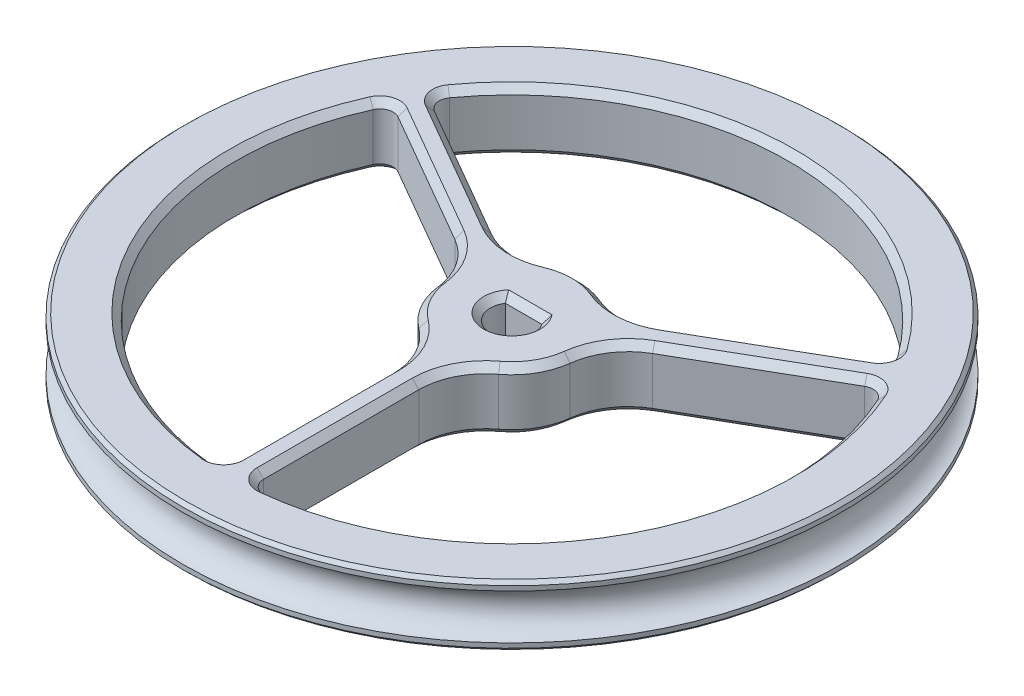
SolidWorks part; units mm, degrees
ref_plane "Front" through (0, 0, 0) normal (0, 0, 1) x (1, 0, 0)
ref_plane "Top" through (0, 0, 0) normal (0, 1, 0) x (1, 0, 0)
ref_plane "Right" through (0, 0, 0) normal (1, 0, 0) x (0, 0, -1)
sketch "Sketch1" plane through (0, 0, 0) normal (0, 1, 0) x (1, 0, 0)
  circle A0 centre (0, 0) radius 24.765
  dimension "D1" = 49.53
extrude "Boss-Extrude1" add sketch "Sketch1" along normal mid plane 4.572
sketch "Sketch2" plane through (0, 0, 0) normal (1, 0, 0) x (0, 0, -1)
  line L0 (0, 0) -> (0, 2.286) construction
  line L2 (0, 0) -> (25.065, 0) construction
  line L3 (24.765, -2.286) -> (24.765, 2.286) construction
  line L4 (24.765, 2.286) -> (-24.765, 2.286) construction
  circle A0 centre (25.065, 0) radius 1.7145
  dimension "D1" = 3.429
  dimension "D2" = 0.3
revolve "Cut-Revolve1" cut sketch "Sketch2" angle 360 about L0
sketch "Sketch3" plane through (0, 2.286, 0) normal (0, 1, 0) x (1, 0, 0)
  line L0 (1.365, 0.8854) -> (1.373, 0.873)
  line L1 (1.373, 0.873) -> (-1.373, 0.873)
  arc A0 (-1.373, 0.873) -> (1.373, 0.873) centre (0, 0) ccw
  dimension "D2" = 3.254
  dimension "D1" = 2.5
extrude "Cut-Extrude1" cut sketch "Sketch3" against normal through all contours L1 A0
sketch "Sketch4" plane through (0, 2.286, 0) normal (0, 1, 0) x (1, 0, 0)
  line L0 (0, 0) -> (21.4471, 12.3825) construction
  line L1 (0, 0) -> (0, 24.765) construction
  line L2 (0, 0) -> (-21.4471, 12.3825) construction
  line L3 (3.7426, 3.3155) -> (17.4622, 11.2365)
  line L4 (-3.7426, 3.3155) -> (-17.4622, 11.2365)
  circle A0 centre (0, 0) radius 24.765 construction
  arc A1 (-3.7426, 3.3155) -> (3.7426, 3.3155) centre (0, 0) cw
  arc A3 (-17.4622, 11.2365) -> (17.4622, 11.2365) centre (0, 0) cw
  dimension "D2" = 4
  dimension "D3" = 5
  dimension "D1" = 120
  dimension "D4" = 2
extrude "Cut-Extrude2" cut sketch "Sketch4" against normal through all
pattern_circular "CirPattern1" count 3 every 120 about axis through (0, 0, 0) along (0, 1, 0) of "Cut-Extrude2"
fillet "Fillet1" radius 5 6 edges at (3.7426, 0, -3.3155) (-3.7426, 0, -3.3155) (4.7426, 0, -1.5835) (1, 0, 4.899) (-1, 0, 4.899) (-4.7426, 0, -1.5835)
fillet "Fillet4" radius 1 6 edges at (17.4622, 0, -11.2365) (18.4622, 0, -9.5044) (-18.4622, 0, -9.5044) (-17.4622, 0, -11.2365) (1, 0, 20.7409) (-1, 0, 20.7409)
chamfer "Chamfer1" distance 0.5 angle 45 4 edges at (0, -2.286, 1.627) (0, -2.286, -0.873) (0, 2.286, 1.627) (0, 2.286, -0.873)
chamfer "Chamfer2" distance 0.5 angle 45 48 edges at (-1, -2.286, 13.8318) (-4.3301, -2.286, 2.5) (-12.4787, -2.286, -6.0499) (-17.983, -2.286, 10.3825) (-11.4787, -2.286, -7.7819) (0, -2.286, -5) (0, -2.286, -20.765) (11.4787, -2.286, -7.7819) (17.983, -2.286, 10.3825) (12.4787, -2.286, -6.0499) (4.3301, -2.286, 2.5) (1, -2.286, 13.8318) (17.983, 2.286, 10.3825) (1, 2.286, 13.8318) (4.3301, 2.286, 2.5) (12.4787, 2.286, -6.0499) (0, 2.286, -20.765) (11.4787, 2.286, -7.7819) (0, 2.286, -5) (-11.4787, 2.286, -7.7819) (-17.983, 2.286, 10.3825) (-1, 2.286, 13.8318) (-4.3301, 2.286, 2.5) (-12.4787, 2.286, -6.0499) (-5.7556, -2.286, -1.5588) (-1.5279, -2.286, 5.7639) (-18.3366, -2.286, -9.0513) (-1.3296, -2.286, 20.4056) (-4.2278, -2.286, -4.2051) (-17.0069, -2.286, -11.3543) (4.2278, -2.286, -4.2051) (17.0069, -2.286, -11.3543) (5.7556, -2.286, -1.5588) (18.3366, -2.286, -9.0513) (1.5279, -2.286, 5.7639) (1.3296, -2.286, 20.4056) (1.3296, 2.286, 20.4056) (1.5279, 2.286, 5.7639) (18.3366, 2.286, -9.0513) (5.7556, 2.286, -1.5588) (17.0069, 2.286, -11.3543) (4.2278, 2.286, -4.2051) (-17.0069, 2.286, -11.3543) (-4.2278, 2.286, -4.2051) (-1.5279, 2.286, 5.7639) (-1.3296, 2.286, 20.4056) (-5.7556, 2.286, -1.5588) (-18.3366, 2.286, -9.0513)
chamfer "Chamfer3" distance 0.25 angle 45 2 edges at (0, -2.286, 24.765) (0, 2.286, 24.765)
